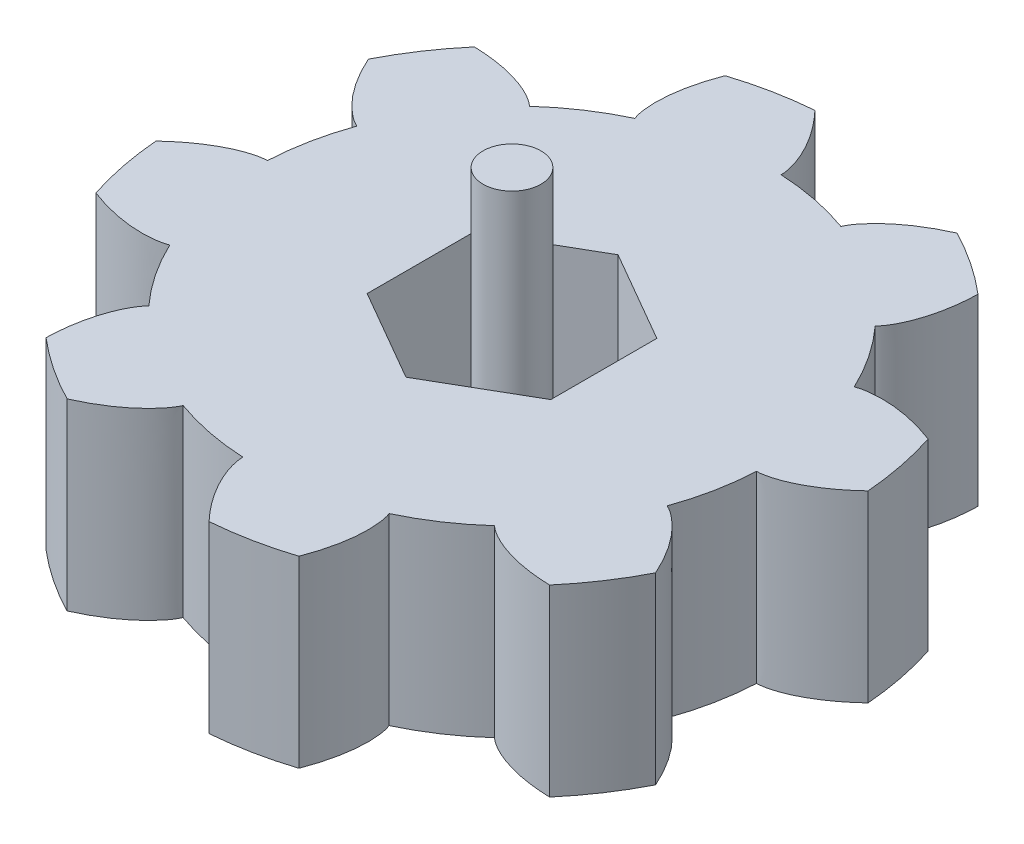
SolidWorks part; units mm, degrees
ref_plane "正面" through (0, 0, 0) normal (0, 0, 1) x (1, 0, 0)
ref_plane "平面" through (0, 0, 0) normal (0, 1, 0) x (1, 0, 0)
ref_plane "右側面" through (0, 0, 0) normal (1, 0, 0) x (0, 0, -1)
sketch "ｽｹｯﾁ1" plane through (0, 0, 0) normal (0, 1, 0) x (1, 0, 0)
  line L0 (0, 0) -> (0, 38.0198) construction
  line L1 (15.9057, 24.8003) -> (-6.7777, 12.25) construction
  line L2 (-14.6737, 16) -> (17.4559, 16) construction
  circle A0 centre (0, 0) radius 16 construction
  circle A1 centre (0, 0) radius 14
  point P7 (0, 16)
  dimension "D1" = 32
  dimension "D2" = 28
  dimension "D3" = 28.955
sketch "ｽｹｯﾁ2" plane through (0, 0, 0) normal (0, 1, 0) x (1, 0, 0)
  line L0 (-6.7777, 12.25) -> (0, 16) construction
  line L1 (-1.074, 13.9587) -> (0.6668, 14.0927) construction
  line L2 (-2.0675, 13.8465) -> (0.6484, 14.252) construction
  line L3 (-3.0504, 13.6636) -> (0.6056, 14.4798) construction
  line L4 (-4.0177, 13.4111) -> (0.5286, 14.7731) construction
  line L5 (-4.9646, 13.0902) -> (0.4079, 15.1278) construction
  line L6 (-5.8862, 12.7025) -> (0.2346, 15.5388) construction
  line L7 (-7.6347, 11.7351) -> (-0.3037, 16.5045) construction
  line L8 (-8.4527, 11.1603) -> (-0.6836, 17.0445) construction
  line L9 (-9.2277, 10.5285) -> (-1.1463, 17.6114) construction
  line L11 (-9.9555, 9.8431) -> (-1.6972, 18.1958) construction
  line L12 (-10.6326, 9.1075) -> (-2.3409, 18.7878) construction
  line L13 (-11.2555, 8.3255) -> (-3.0811, 19.3768) construction
  line L14 (14, 0) -> (16, 0) construction
  line L15 (16, 0) -> (18, 0) construction
  line L16 (0, 0) -> (-7.7455, 38.9391) construction
  line L17 (0, 0) -> (0, 38.0198) construction
  arc A0 (-6.7777, 12.25) -> (-5.8862, 12.7025) centre (0, 0) cw
  arc A1 (-5.8862, 12.7025) -> (-4.9646, 13.0902) centre (0, 0) cw
  arc A2 (-4.9646, 13.0902) -> (-4.0177, 13.4111) centre (0, 0) cw
  circle A3 centre (0, 0) radius 14 construction
  arc A4 (-4.0177, 13.4111) -> (-3.0504, 13.6636) centre (0, 0) cw
  arc A5 (-3.0504, 13.6636) -> (-2.0675, 13.8465) centre (0, 0) cw
  arc A6 (-6.7777, 12.25) -> (-7.6347, 11.7351) centre (0, 0) ccw
  arc A7 (-7.6347, 11.7351) -> (-8.4527, 11.1603) centre (0, 0) ccw
  arc A8 (-8.4527, 11.1603) -> (-9.2277, 10.5285) centre (0, 0) ccw
  arc A9 (-9.2277, 10.5285) -> (-9.9555, 9.8431) centre (0, 0) ccw
  arc A10 (-9.9555, 9.8431) -> (-10.6326, 9.1075) centre (0, 0) ccw
  arc A11 (-2.0675, 13.8465) -> (-1.074, 13.9587) centre (0, 0) cw
  arc A12 (-10.6326, 9.1075) -> (-11.2555, 8.3255) centre (0, 0) ccw
  arc A13 (-6.7777, 12.25) -> (0.6707, 13.9839) centre (0, 0) cw construction
  circle A15 centre (0, 0) radius 18 construction
  circle A16 centre (0, 0) radius 16 construction
  spline S0 degree 3 poles (-3.0811, 19.3768) (-2.5933, 19.0158) (-1.9238, 18.449) (-1.1551, 17.6353) (-0.6914, 17.0685) (-0.3105, 16.5285) (-0.0058, 16.024) (0.2297, 15.5628) (0.404, 15.1518) (0.5255, 14.7971) (0.6035, 14.5038) (0.6537, 14.2402) (0.6712, 14.0738) (0.6707, 13.9839) knots 0 0 0 0 0.269826 0.388862 0.497313 0.595179 0.682461 0.759157 0.825269 0.880797 0.925739 0.960097 1 1 1 1
  spline S1 degree 3 poles (-4.5686, 19.0809) (-4.8812, 18.5607) (-5.2828, 17.7809) (-5.6815, 16.735) (-5.893, 16.0339) (-6.0384, 15.3892) (-6.1268, 14.8065) (-6.1678, 14.2902) (-6.1716, 13.8438) (-6.1481, 13.4696) (-6.1079, 13.1688) (-6.0534, 12.9061) (-6.0059, 12.7456) (-5.971, 12.6628) knots 0 0 0 0 0.269826 0.388862 0.497313 0.595179 0.682461 0.759157 0.825269 0.880797 0.925739 0.960097 1 1 1 1
  point P39 (-1.4479, 17.9417)
  point P55 (-5.5283, 17.13)
  dimension "D1" = 7.746
  dimension "D3" = 6.746
  dimension "D4" = 5.746
  dimension "D5" = 4.746
  dimension "D6" = 3.746
  dimension "D7" = 2.746
  dimension "D8" = 1.746
  dimension "D9" = 8.746
  dimension "D10" = 9.746
  dimension "D11" = 10.746
  dimension "D12" = 11.746
  dimension "D13" = 12.746
  dimension "D14" = 13.746
  dimension "D15" = 11.25
  dimension "D2" = 1
sketch "ｽｹｯﾁ3" plane through (0, 0, 0) normal (0, 1, 0) x (1, 0, 0)
  arc A0 (0.6707, 13.9839) -> (-5.971, 12.6628) centre (0, 0) ccw
  arc A1 (-1.4479, 17.9417) -> (-5.5283, 17.13) centre (0, 0) ccw
  circle A2 centre (0, 0) radius 14 construction
  circle A3 centre (0, 0) radius 18 construction
  spline S0 degree 3 poles (-5.5283, 17.13) (-5.6694, 16.7633) (-5.8602, 16.1794) (-6.0384, 15.3892) (-6.1268, 14.8065) (-6.1678, 14.2902) (-6.1716, 13.8438) (-6.1481, 13.4696) (-6.1079, 13.1688) (-6.0534, 12.9061) (-6.0059, 12.7456) (-5.971, 12.6628) knots 0 0 0 0 0.25795 0.402417 0.531259 0.644476 0.742069 0.824036 0.890379 0.941097 1 1 1 1
  spline S1 degree 3 poles (-1.4479, 17.9417) (-1.1772, 17.6569) (-0.7775, 17.1904) (-0.3105, 16.5285) (-0.0058, 16.024) (0.2297, 15.5628) (0.404, 15.1518) (0.5255, 14.7971) (0.6035, 14.5038) (0.6537, 14.2402) (0.6712, 14.0738) (0.6707, 13.9839) knots 0 0 0 0 0.25795 0.402417 0.531259 0.644476 0.742069 0.824036 0.890379 0.941097 1 1 1 1
extrude "ﾎﾞｽ - 押し出し1" add sketch "ｽｹｯﾁ1" along normal blind 10
extrude "ﾎﾞｽ - 押し出し2" add sketch "ｽｹｯﾁ3" along normal blind 10
pattern_circular "円形ﾊﾟﾀｰﾝ1" count 8 over 360 about axis through (0, 10, 0) along (0, 1, 0) of "ﾎﾞｽ - 押し出し2"
sketch "ｽｹｯﾁ6" plane through (0, 10, 0) normal (0, 1, 0) x (1, 0, 0)
  line L1 (0, 5.7735) -> (-5, 2.8868)
  line L2 (-5, 2.8868) -> (-5, -2.8868)
  line L3 (-5, -2.8868) -> (0, -5.7735)
  line L4 (0, -5.7735) -> (5, -2.8868)
  line L5 (5, -2.8868) -> (5, 2.8868)
  line L6 (5, 2.8868) -> (0, 5.7735)
  circle A0 centre (0, 0) radius 5 construction
  point P1 (0, 0)
  point P10 (0, 0)
  dimension "D1" = 10
extrude "ｶｯﾄ - 押し出し2" cut sketch "ｽｹｯﾁ6" against normal offset from surface (8 mm away) 2 up to face at (0, 0, 0)
sketch "ｽｹｯﾁ8" plane through (0, 2, 0) normal (0, 1, 0) x (1, 0, 0)
  circle A0 centre (0, 0) radius 1.575
  dimension "D1" = 3.15
extrude "ﾎﾞｽ - 押し出し5" add sketch "ｽｹｯﾁ8" along normal blind 15
equation "\"D3@ｽｹｯﾁ2\"=\"D1@ｽｹｯﾁ2\"-1"
equation "\"D4@ｽｹｯﾁ2\"=\"D1@ｽｹｯﾁ2\"-2"
equation "\"D5@ｽｹｯﾁ2\"=\"D1@ｽｹｯﾁ2\"-3"
equation "\"D6@ｽｹｯﾁ2\"=\"D1@ｽｹｯﾁ2\"-4"
equation "\"D7@ｽｹｯﾁ2\"=\"D1@ｽｹｯﾁ2\"-5"
equation "\"D8@ｽｹｯﾁ2\"=\"D1@ｽｹｯﾁ2\"-6"
equation "\"D9@ｽｹｯﾁ2\"=\"D1@ｽｹｯﾁ2\"+1"
equation "\"D10@ｽｹｯﾁ2\"=\"D1@ｽｹｯﾁ2\"+2"
equation "\"D11@ｽｹｯﾁ2\"=\"D1@ｽｹｯﾁ2\"+3"
equation "\"D12@ｽｹｯﾁ2\"=\"D1@ｽｹｯﾁ2\"+4"
equation "\"D13@ｽｹｯﾁ2\"=\"D1@ｽｹｯﾁ2\"+5"
equation "\"D14@ｽｹｯﾁ2\"=\"D1@ｽｹｯﾁ2\"+6"
equation "\"D15@ｽｹｯﾁ2\"=90/8"
